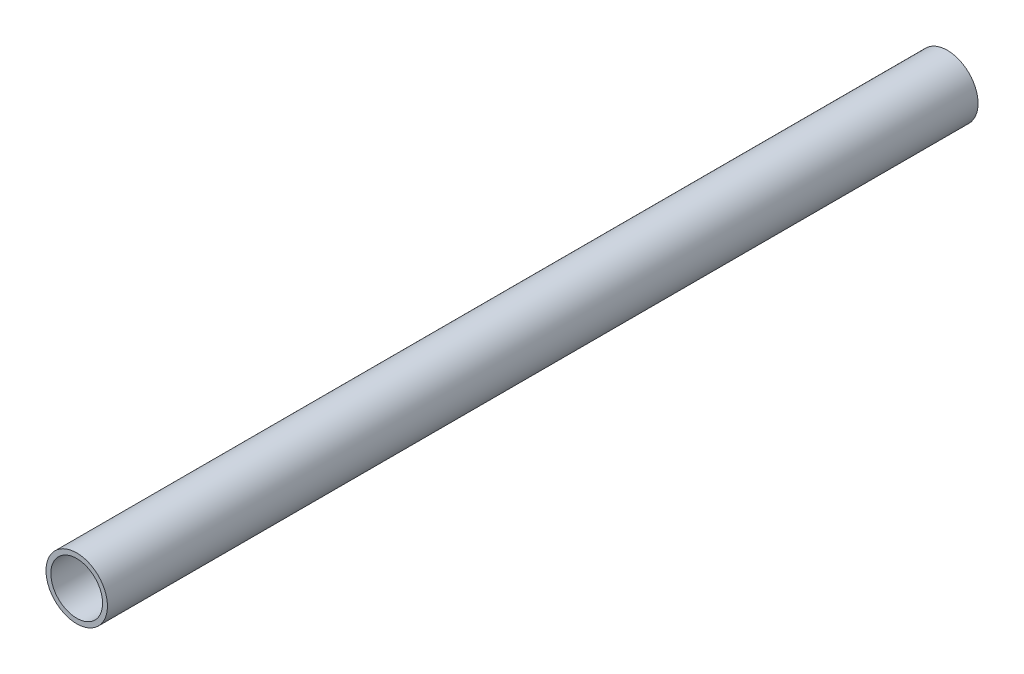
SolidWorks part; units mm, degrees
ref_plane "Alzado" through (0, 0, 0) normal (0, 0, 1) x (1, 0, 0)
ref_plane "Planta" through (0, 0, 0) normal (0, 1, 0) x (1, 0, 0)
ref_plane "Vista lateral" through (0, 0, 0) normal (1, 0, 0) x (0, 0, -1)
sketch "Croquis2" plane through (0, 0, 0) normal (0, 0, 1) x (1, 0, 0)
  circle A0 centre (0, 0) radius 6.35
  circle A1 centre (0, 0) radius 5.35
  dimension "D1" = 12.7
  dimension "D2" = 1
extrude "Saliente-Extruir1" add sketch "Croquis2" along normal blind 180
